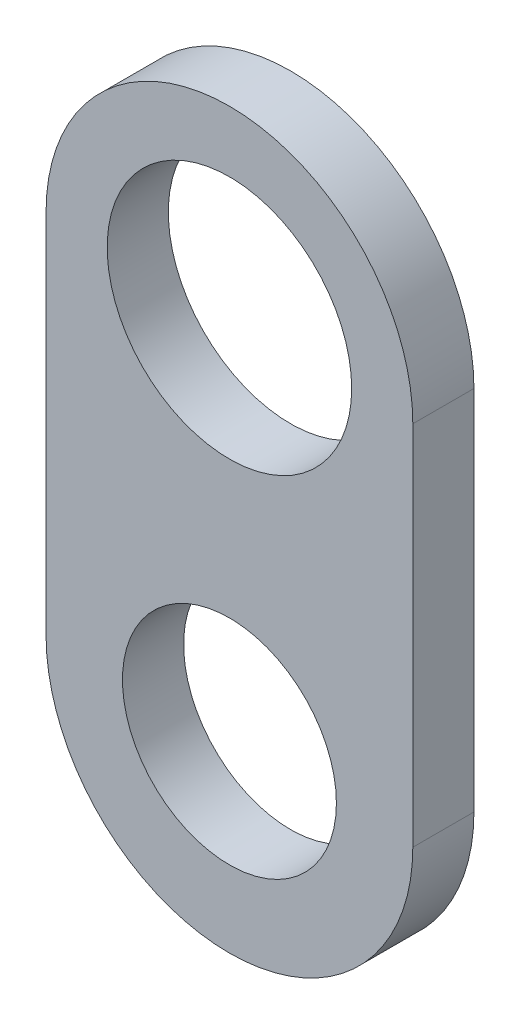
SolidWorks part; units mm, degrees
material "6061-T6 (SS)"
ref_plane "Front Plane" through (0, 0, 0) normal (0, 0, 1) x (1, 0, 0)
ref_plane "Top Plane" through (0, 0, 0) normal (0, 1, 0) x (1, 0, 0)
ref_plane "Right Plane" through (0, 0, 0) normal (1, 0, 0) x (0, 0, -1)
sketch "Sketch1" plane through (0, 0, 0) normal (0, 0, 1) x (1, 0, 0)
  line L0 (-750, 0) -> (-750, -1500)
  line L1 (750, 0) -> (750, -1500)
  arc A0 (750, 0) -> (-750, 0) centre (0, 0) ccw
  arc A1 (-750, -1500) -> (750, -1500) centre (0, -1500) ccw
  dimension "D1" = 1500
  dimension "D2" = 1500
  dimension "D3" = 1500
extrude "Boss-Extrude1" add sketch "Sketch1" along normal blind 250
sketch "Sketch2" plane through (0, 0, 250) normal (0, 0, 1) x (1, 0, 0)
  circle A0 centre (0, 0) radius 500
  circle A1 centre (0, -1500) radius 437.5
  dimension "D1" = 1000
  dimension "D2" = 875
  dimension "D3" = 1500
extrude "Cut-Extrude1" cut sketch "Sketch2" against normal blind 250
